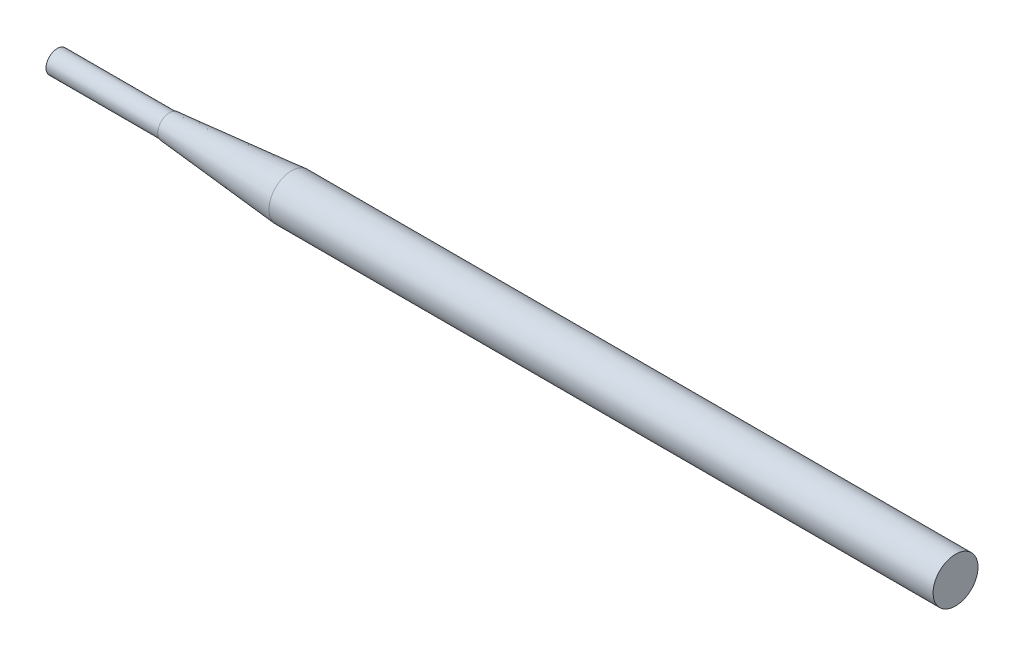
SolidWorks part; units mm, degrees
ref_plane "Front Plane" through (0, 0, 0) normal (0, 0, 1) x (1, 0, 0)
ref_plane "Top Plane" through (0, 0, 0) normal (0, 1, 0) x (1, 0, 0)
ref_plane "Right Plane" through (0, 0, 0) normal (1, 0, 0) x (0, 0, -1)
sketch "Sketch1" plane through (0, 0, 0) normal (1, 0, 0) x (0, 0, -1)
  circle A0 centre (0, 0) radius 10
  dimension "D1" = 20
extrude "Boss-Extrude1" add sketch "Sketch1" along normal blind 100
sketch "Sketch2" plane through (100, 0, 0) normal (1, 0, 0) x (0, 0, -1)
  circle A0 centre (0, 0) radius 20
  dimension "D1" = 40
extrude "Boss-Extrude3" add sketch "Sketch2" along normal blind 700
sketch "Sketch4" plane through (100, 0, 0) normal (-1, 0, 0) x (0, 0, 1)
  circle A0 centre (0, 0) radius 10.5
  dimension "D1" = 21
extrude "Cut-Extrude2" cut sketch "Sketch4" against normal blind 700 draft 5 flip side to cut
